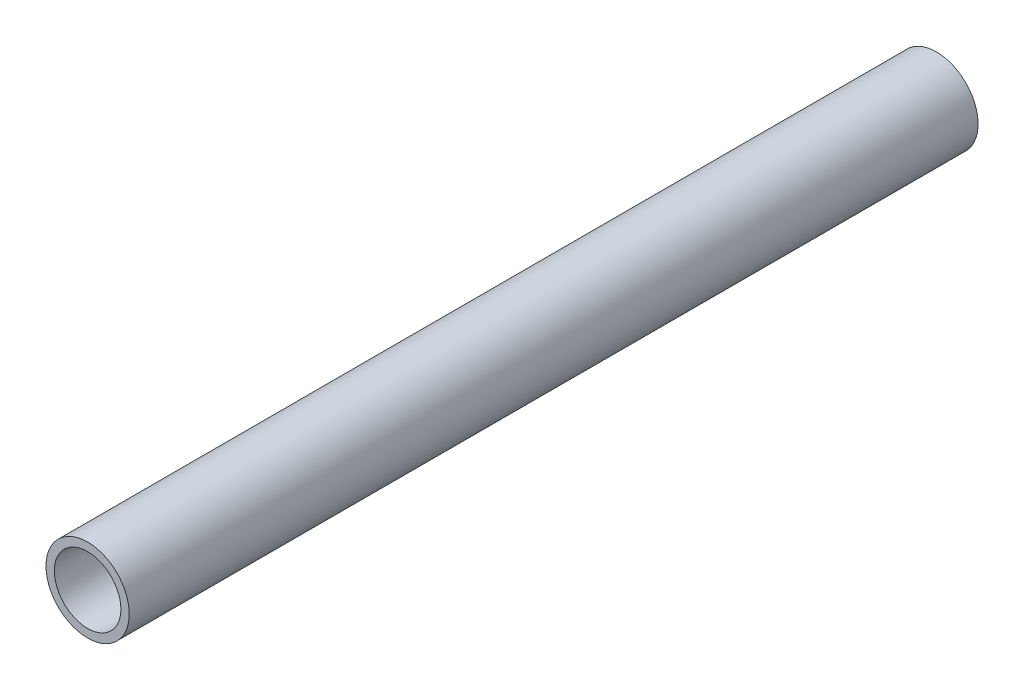
SolidWorks part; units mm, degrees
ref_plane "Front Plane" through (0, 0, 0) normal (0, 0, 1) x (1, 0, 0)
ref_plane "Top Plane" through (0, 0, 0) normal (0, 1, 0) x (1, 0, 0)
ref_plane "Right Plane" through (0, 0, 0) normal (1, 0, 0) x (0, 0, -1)
sketch "Sketch1" plane through (0, 0, 0) normal (0, 0, 1) x (1, 0, 0)
  circle A0 centre (0, 0) radius 4
  circle A1 centre (0, 0) radius 5
extrude "Boss-Extrude1" add sketch "Sketch1" along normal blind 100
sketch "Sketch6" plane through (0, 0, 0) normal (0, 0, -1) x (-1, 0, 0)
  circle A0 centre (0, 0) radius 5
extrude "Boss-Extrude2" add sketch "Sketch6" along normal blind 2
